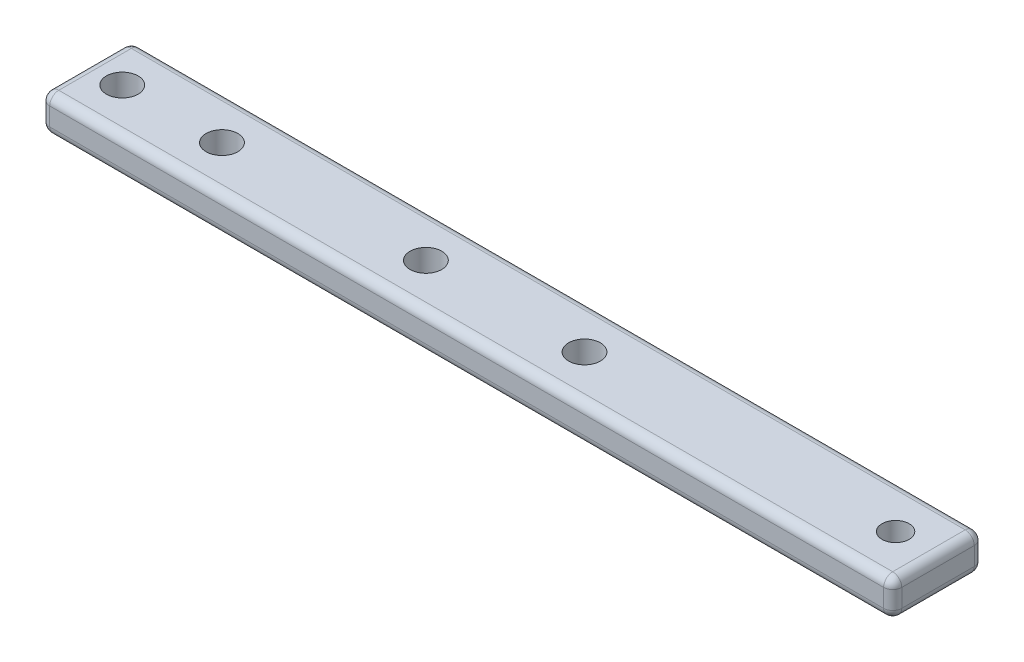
SolidWorks part; units mm, degrees
ref_plane "Front Plane" through (0, 0, 0) normal (0, 0, 1) x (1, 0, 0)
ref_plane "Top Plane" through (0, 0, 0) normal (0, 1, 0) x (1, 0, 0)
ref_plane "Right Plane" through (0, 0, 0) normal (1, 0, 0) x (0, 0, -1)
sketch "Sketch1" plane through (0, 0, 0) normal (0, 1, 0) x (1, 0, 0)
  line L1 (-30, 5) -> (30, 5)
  line L2 (-30, 5) -> (-30, -5)
  line L3 (-30, -5) -> (30, -5)
  line L4 (30, 5) -> (30, -5)
  line L5 (-30, 5) -> (30, -5) construction
  line L6 (-30, -5) -> (30, 5) construction
  point P1 (0, 0)
  dimension "D1" = 60
  dimension "D2" = 10
extrude "Boss-Extrude1" add sketch "Sketch1" along normal blind 4
sketch "Sketch2" plane through (0, 4, 0) normal (0, 1, 0) x (1, 0, 0)
  line L0 (30, -5) -> (30, 5) construction
  line L1 (-30, 5) -> (-30, -5) construction
  line L2 (30, 5) -> (-30, 5) construction
  circle A0 centre (-26, 0) radius 1.75
  circle A1 centre (7.5, 0) radius 1.75
  circle A2 centre (25, 0) radius 1.75
  circle A3 centre (-15, 0) radius 1.75
  dimension "D1" = 3.5
  dimension "D2" = 3.5
  dimension "D3" = 3.5
  dimension "D11" = 3.5
  dimension "D4" = 5
  dimension "D5" = 4
  dimension "D6" = 37.5
  dimension "D7" = 5
  dimension "D8" = 5
  dimension "D9" = 5
  dimension "D10" = 22.5
  dimension "D12" = 15
extrude "Cut-Extrude1" cut sketch "Sketch2" against normal blind 4
sketch "Sketch3" plane through (30, 0, 0) normal (1, 0, 0) x (0, 0, -1)
  line L1 (-5, 4) -> (5, 4)
  line L2 (-5, 4) -> (-5, 0)
  line L3 (-5, 0) -> (5, 0)
  line L4 (5, 4) -> (5, 0)
extrude "Boss-Extrude2" add sketch "Sketch3" along normal blind 40
sketch "Sketch4" plane through (0, 4, 0) normal (0, 1, 0) x (1, 0, 0)
  line L1 (70, 5) -> (70, -5) construction
  circle A0 centre (59.32, 0) radius 1.5
  dimension "D1" = 3
  dimension "D2" = 9.18
extrude "Cut-Extrude2" cut sketch "Sketch4" against normal blind 10
sketch "Sketch5" plane through (0, 0, 5) normal (0, 0, 1) x (1, 0, 0)
  line L0 (-30, 0) -> (70, 0) construction
  line L1 (70, 4) -> (64, 4)
  line L2 (70, 4) -> (70, 0)
  line L3 (70, 0) -> (64, 0)
  line L4 (64, 4) -> (64, 0)
  dimension "D1" = 6
extrude "Cut-Extrude3" cut sketch "Sketch5" against normal through all both and the other way through all
fillet "Fillet1" radius 1 12 edges at (-30, 0, 0) (-30, 4, 0) (-30, 2, -5) (17, 4, -5) (17, 0, -5) (64, 0, 0) (64, 4, 0) (64, 2, -5) (-30, 2, 5) (17, 0, 5) (17, 4, 5) (64, 2, 5)
